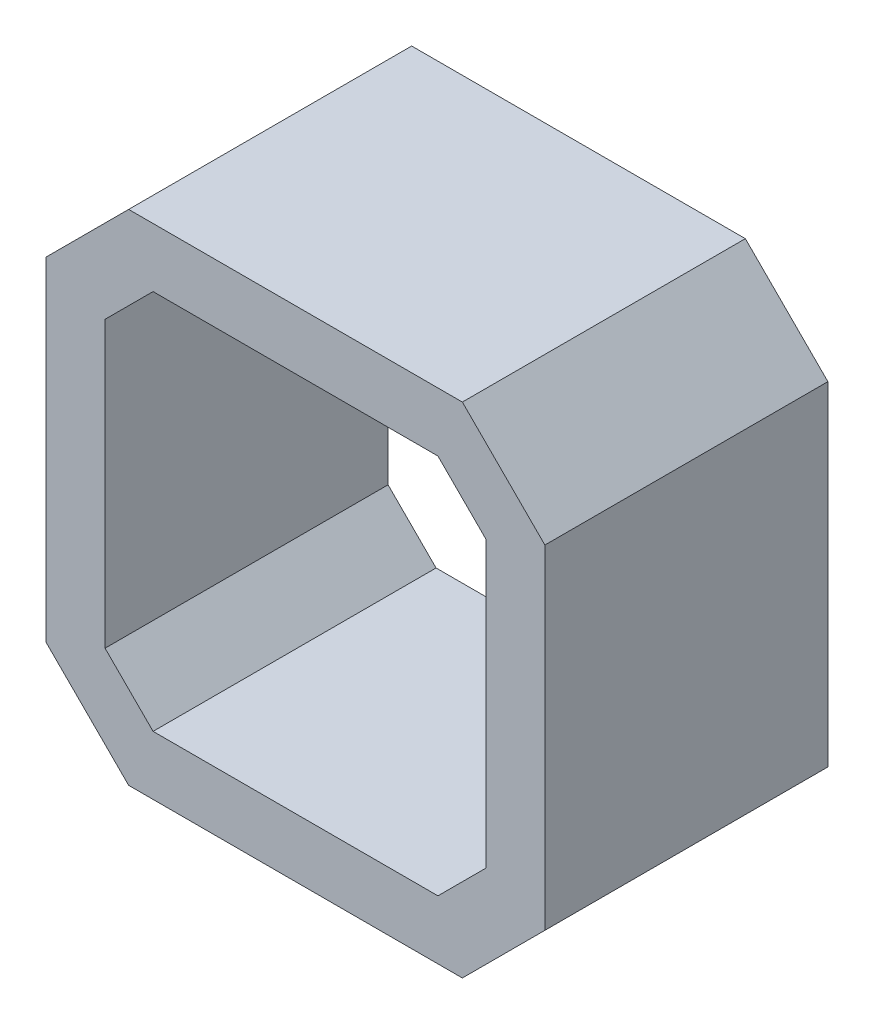
SolidWorks part; units mm, degrees
ref_plane "Plano frontal" through (0, 0, 0) normal (0, 0, 1) x (1, 0, 0)
ref_plane "Plano superior" through (0, 0, 0) normal (0, 1, 0) x (1, 0, 0)
ref_plane "Plano direito" through (0, 0, 0) normal (1, 0, 0) x (0, 0, -1)
sketch "Esboço1" plane through (0, 0, 0) normal (0, 0, 1) x (1, 0, 0)
  line L0 (-14.15, 21.15) -> (-21.15, 14.15)
  line L1 (14.15, -21.15) -> (-14.15, -21.15)
  line L2 (21.15, -14.15) -> (21.15, 14.15)
  line L3 (14.15, 21.15) -> (-14.15, 21.15)
  line L4 (-21.15, -14.15) -> (-21.15, 14.15)
  line L5 (21.15, -21.15) -> (-21.15, 21.15) construction
  line L6 (21.15, 21.15) -> (-21.15, -21.15) construction
  line L7 (21.15, 14.15) -> (14.15, 21.15)
  line L8 (-14.15, -21.15) -> (-21.15, -14.15)
  line L9 (21.15, -14.15) -> (14.15, -21.15)
  line L10 (12.0789, 16.15) -> (-12.0789, 16.15)
  line L11 (-12.0789, 16.15) -> (-16.15, 12.0789)
  line L12 (-16.15, -12.0789) -> (-16.15, 12.0789)
  line L13 (-12.0789, -16.15) -> (-16.15, -12.0789)
  line L14 (12.0789, -16.15) -> (-12.0789, -16.15)
  line L15 (16.15, -12.0789) -> (12.0789, -16.15)
  line L16 (16.15, -12.0789) -> (16.15, 12.0789)
  line L17 (16.15, 12.0789) -> (12.0789, 16.15)
  point P0 (0, 0)
  dimension "D1" = 42.3
  dimension "D2" = 42.3
  dimension "D7" = 5
extrude "Ressalto-extrusão2" add sketch "Esboço1" along normal blind 24
